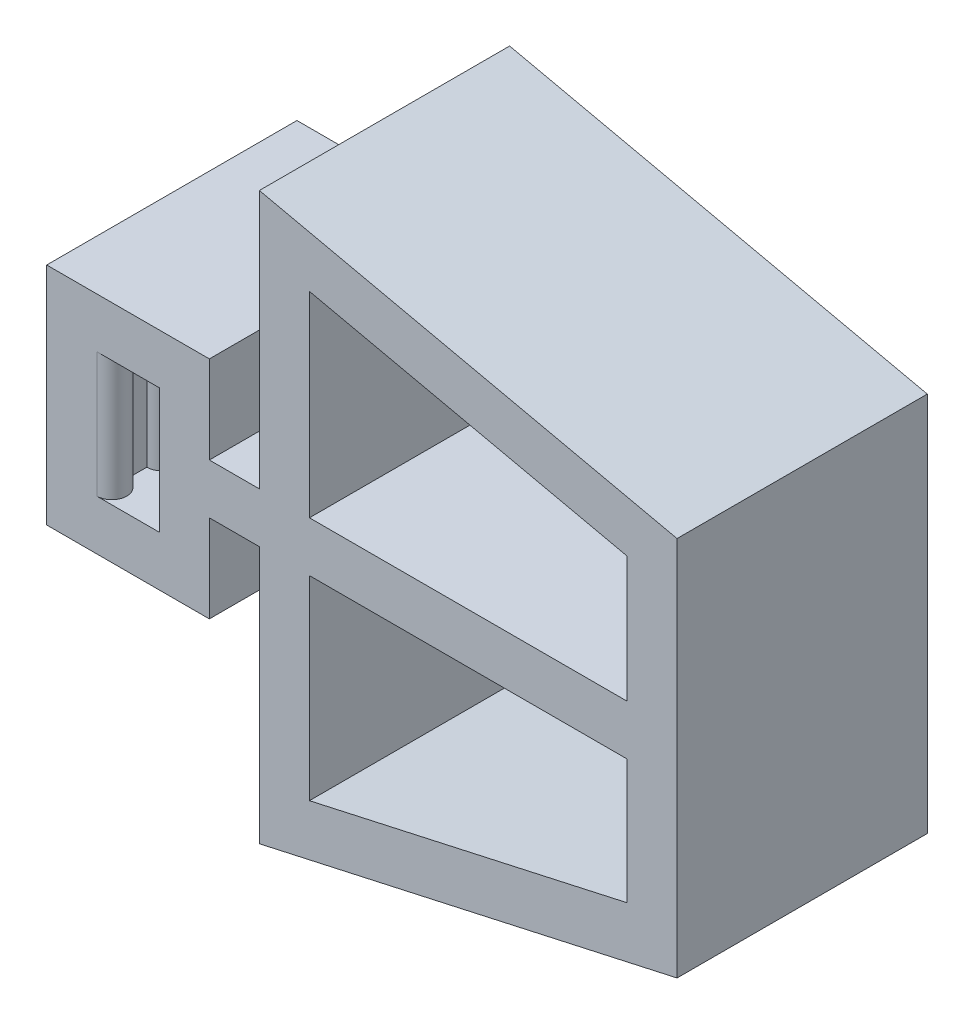
SolidWorks part; units mm, degrees
ref_plane "Front Plane" through (0, 0, 0) normal (0, 0, 1) x (1, 0, 0)
ref_plane "Top Plane" through (0, 0, 0) normal (0, 1, 0) x (1, 0, 0)
ref_plane "Right Plane" through (0, 0, 0) normal (1, 0, 0) x (0, 0, -1)
sketch "Sketch1" plane through (0, 0, 0) normal (0, 0, 1) x (1, 0, 0)
  line L0 (49.8058, -29.5274) -> (49.8058, -52.1387)
  line L1 (49.8058, -52.1387) -> (66.4977, -48.4382)
  line L2 (66.4977, -48.4382) -> (66.4977, -33.2279)
  line L3 (66.4977, -33.2279) -> (49.8058, -29.5274)
  line L4 (51.8058, -39.8565) -> (64.4977, -39.8565)
  line L5 (64.4977, -39.8565) -> (64.4977, -41.8565)
  line L6 (64.4977, -41.8565) -> (51.8058, -41.8565)
  line L7 (51.8058, -41.8565) -> (51.8058, -39.8565)
  line L8 (51.8058, -32.0193) -> (51.8058, -49.6468)
  line L9 (51.8058, -49.6468) -> (64.4977, -46.8331)
  line L10 (64.4977, -46.8331) -> (64.4977, -34.8331)
  line L11 (64.4977, -34.8331) -> (51.8058, -32.0193)
  line L12 (49.8058, -39.8565) -> (47.8058, -39.8565)
  line L13 (47.8058, -39.8565) -> (47.8058, -36.3565)
  line L14 (47.8058, -36.3565) -> (41.3058, -36.3565)
  line L15 (41.3058, -36.3565) -> (41.3058, -45.3565)
  line L16 (41.3058, -45.3565) -> (47.8058, -45.3565)
  line L17 (47.8058, -45.3565) -> (47.8058, -41.8565)
  line L18 (47.8058, -41.8565) -> (49.8058, -41.8565)
  line L20 (43.3058, -38.3565) -> (45.8058, -38.3565)
  line L21 (43.3058, -38.3565) -> (43.3058, -43.3565)
  line L22 (43.3058, -43.3565) -> (45.8058, -43.3565)
  line L23 (45.8058, -38.3565) -> (45.8058, -43.3565)
  point P7 (51.8058, -40.8565)
  dimension "D1" = 77.5
  dimension "D2" = 102.5
  dimension "D3" = 12
  dimension "D4" = 13
  dimension "D5" = 17.6274
  dimension "D6" = 13
  dimension "D7" = 77.5
  dimension "D8" = 102.5
  dimension "D9" = 2
  dimension "D10" = 2
  dimension "D11" = 2
  dimension "D12" = 2
  dimension "D13" = 1
  dimension "D14" = 1
  dimension "D15" = 2
  dimension "D16" = 2
  dimension "D17" = 7.8371
  dimension "D18" = 2
  dimension "D19" = 2
  dimension "D20" = 2
  dimension "D21" = 2
  dimension "D22" = 3.5
  dimension "D23" = 3.5
  dimension "D24" = 7.7903
  dimension "D25" = 2.5
extrude "Boss-Extrude1" add sketch "Sketch1" along normal blind 10 contours L17 L18 L0 L12 L13 L14 L15 L16 L20 L23 L22 L21 | L2 L3 L0 L1 L11 L10 L5 L9 L8 L7 | L7 L6 L5 L4
sketch "Sketch2" plane through (0, -38.3565, 0) normal (0, -1, 0) x (1, 0, 0)
  line L0 (43.3058, 10) -> (43.3058, 0) construction
  line L1 (43.3058, 8.8) -> (43.3058, 10)
  arc A0 (43.3058, 10) -> (43.3058, 8.8) centre (43.3058, 9.4) cw
  dimension "D1" = 0.6
extrude "Boss-Extrude2" add sketch "Sketch2" along normal blind 5
pattern_linear "LPattern1" count 5 spacing 2 along (0, 0, -1) of "Boss-Extrude2"
